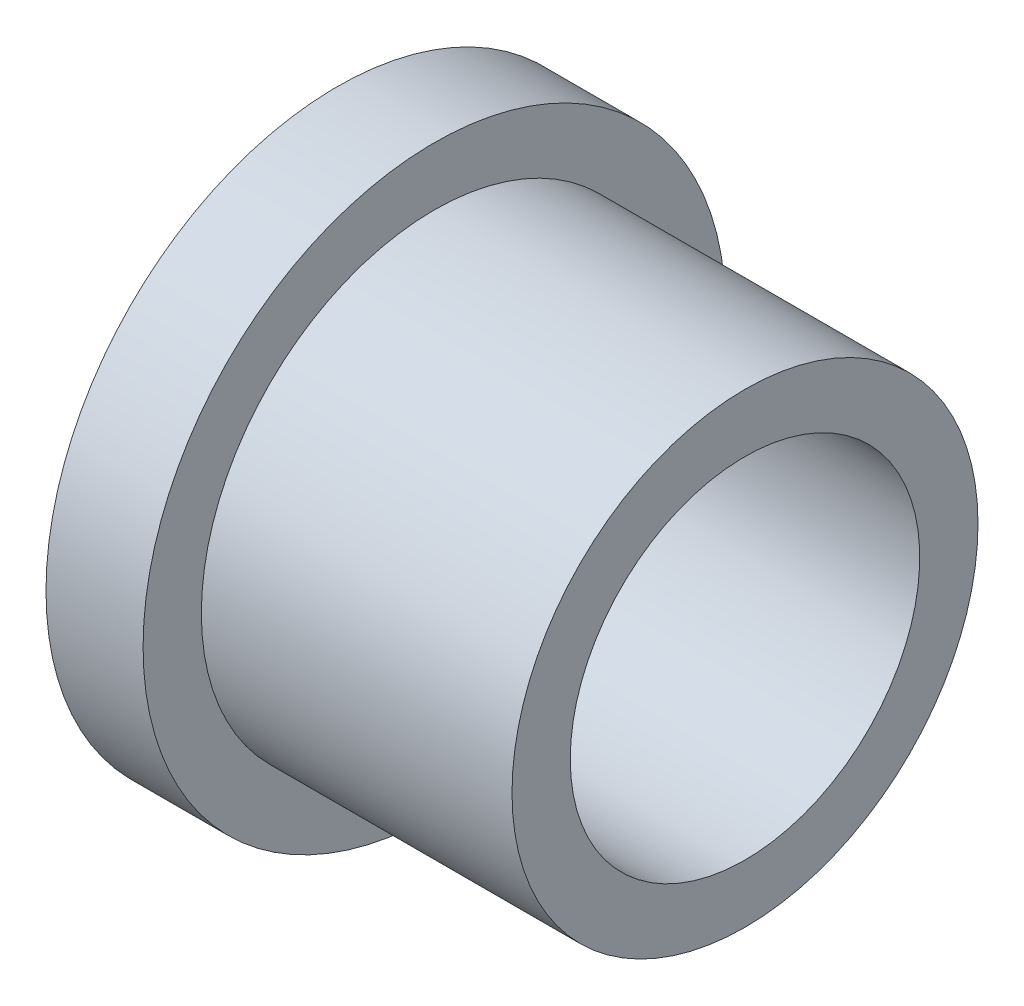
SolidWorks part; units mm, degrees
ref_plane "Front Plane" through (0, 0, 0) normal (0, 0, 1) x (1, 0, 0)
ref_plane "Top Plane" through (0, 0, 0) normal (0, 1, 0) x (1, 0, 0)
ref_plane "Right Plane" through (0, 0, 0) normal (1, 0, 0) x (0, 0, -1)
sketch "Sketch1" plane through (0, 0, 0) normal (0, 0, 1) x (1, 0, 0)
  line L0 (0, 0) -> (28.274, 0) construction
  line L1 (0, 9) -> (21, 9)
  line L2 (21, 9) -> (21, 12)
  line L3 (21, 12) -> (5, 12)
  line L4 (5, 12) -> (5, 15)
  line L5 (5, 15) -> (0, 15)
  line L6 (0, 15) -> (0, 9)
  point P5 (0, 0)
  dimension "D1" = 16
  dimension "D2" = 21
  dimension "D3" = 3
  dimension "D4" = 24
  dimension "D5" = 30
revolve "Revolve1" add sketch "Sketch1" angle 360 about L0
